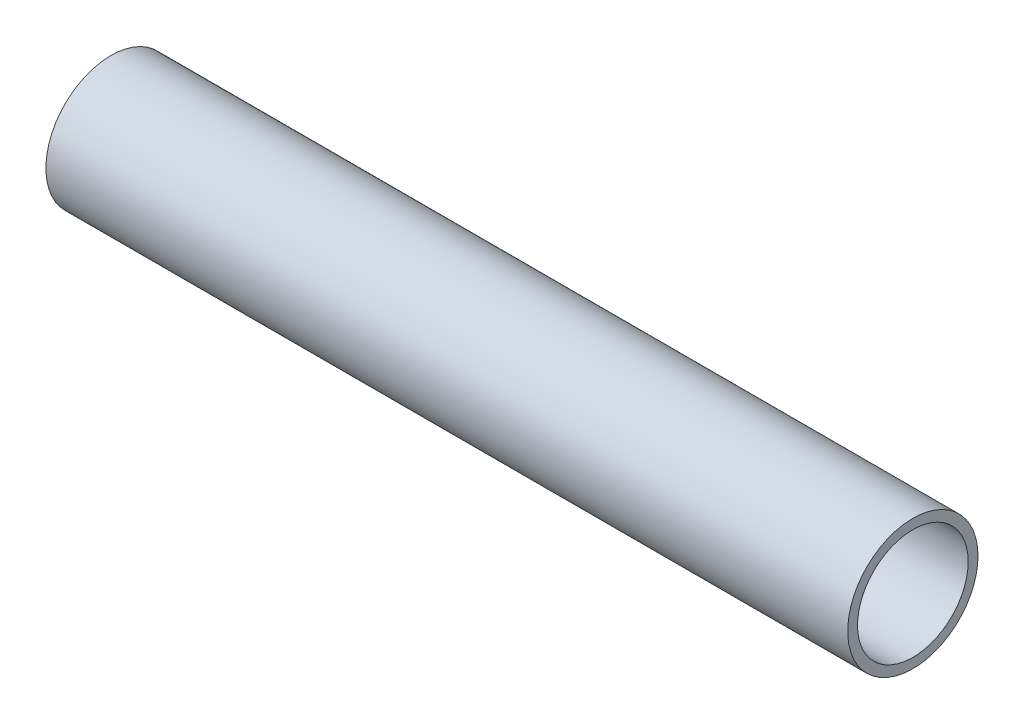
SolidWorks part; units mm, degrees
ref_plane "Front Plane" through (0, 0, 0) normal (0, 0, 1) x (1, 0, 0)
ref_plane "Top Plane" through (0, 0, 0) normal (0, 1, 0) x (1, 0, 0)
ref_plane "Right Plane" through (0, 0, 0) normal (1, 0, 0) x (0, 0, -1)
sketch "Sketch1" plane through (0, 0, 0) normal (1, 0, 0) x (0, 0, -1)
  circle A0 centre (0, 0) radius 20.6375
  circle A1 centre (0, 0) radius 17.526
  dimension "D1" = 41.275
extrude "Boss-Extrude1" add sketch "Sketch1" along normal blind 254
